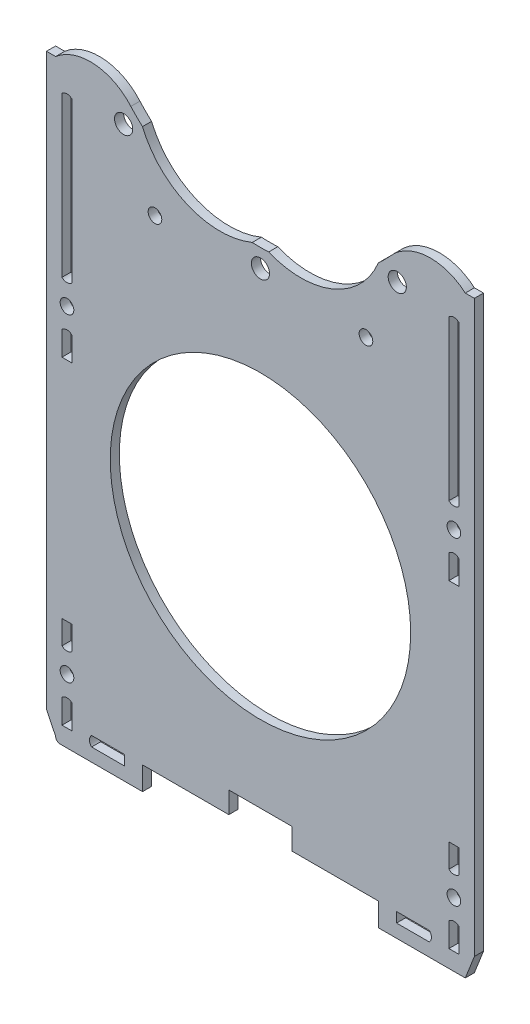
SolidWorks part; units mm, degrees
ref_plane "前视基准面" through (0, 0, 0) normal (0, 0, 1) x (1, 0, 0)
ref_plane "上视基准面" through (0, 0, 0) normal (0, 1, 0) x (1, 0, 0)
ref_plane "右视基准面" through (0, 0, 0) normal (1, 0, 0) x (0, 0, -1)
sketch "草图3" plane through (0, 0, 0) normal (0, 0, 1) x (1, 0, 0)
  line L0 (-37, -95.9902) -> (-37, -96.0902) construction
  line L5 (-37, -93.9902) -> (-30, -93.9902) construction
  line L6 (-37, -93.9902) -> (-37, -95.9902) construction
  line L7 (-37, -95.9902) -> (-30, -95.9902) construction
  line L8 (-30, -93.9902) -> (-30, -95.9902) construction
  line L9 (-37, -96.0902) -> (-37.1, -96.0902) construction
  line L12 (-42.5, -14.9402) -> (-41.8015, -14.9402) construction
  line L19 (-37.1, -96.0902) -> (-29.9, -96.0902)
  line L21 (-37.1, -93.8902) -> (-29.9, -93.8902)
  line L22 (-29.9, -96.0902) -> (-29.9, -93.8902)
  line L111 (-43.6, -9.9902) -> (-43.6, 25.0098)
  line L119 (-41.4, -19.8902) -> (-41.4, -25.1902)
  line L120 (-41.4, -25.1902) -> (-43.6, -25.1902)
  line L121 (-43.6, -25.1902) -> (-43.6, -19.8902)
  line L122 (-47, 31.3171) -> (-47, -93.8902)
  line L124 (37.1, -93.8902) -> (29.9, -93.8902)
  line L136 (37.1, -96.0902) -> (29.9, -96.0902)
  line L147 (30, -93.9902) -> (30, -95.9902) construction
  line L148 (29.9, -96.0902) -> (29.9, -93.8902)
  line L152 (-41.4, 25.0098) -> (-41.4, -9.9902)
  line L153 (37, -96.0902) -> (37.1, -96.0902) construction
  line L154 (37, -93.9902) -> (37, -95.9902) construction
  line L155 (37, -95.9902) -> (37, -96.0902) construction
  line L157 (43.6, -25.1902) -> (43.6, -19.8902)
  line L158 (41.4, -25.1902) -> (43.6, -25.1902)
  line L159 (41.4, -19.8902) -> (41.4, -25.1902)
  line L171 (-25.9, -97.9902) -> (-25.9, -93.8902)
  line L172 (-25.9, -93.8902) -> (-15.9, -93.8902)
  line L180 (0, 10.5098) -> (0, 13.5) construction
  line L181 (-15.9, -93.8902) -> (-6.949, -93.8902)
  line L182 (-6.949, -93.8902) -> (-6.949, -89.1902)
  line L183 (-6.949, -89.1902) -> (6.949, -89.1902)
  line L184 (6.949, -93.8902) -> (6.949, -89.1902)
  line L185 (15.9, -93.8902) -> (6.949, -93.8902)
  line L186 (25.9, -93.8902) -> (15.9, -93.8902)
  line L187 (25.9, -97.9902) -> (25.9, -93.8902)
  line L195 (-25.9, -97.9902) -> (-25.9, -98.9902)
  line L196 (-25.9, -98.9902) -> (-45, -98.9902) construction
  line L197 (-45, -98.9902) -> (-45, -97.9902) construction
  line L198 (25.9, -97.9902) -> (25.9, -98.9902)
  line L199 (25.9, -98.9902) -> (45, -98.9902)
  line L209 (42.5, -9.9902) -> (42.5, -19.8902) construction
  line L210 (-44, -98.9902) -> (-25.9, -98.9902)
  line L212 (0, 56) -> (31.4326, 27.3951) construction
  line L213 (0, 56) -> (28.5728, 24.6019) construction
  line L218 (-45, 31.3171) -> (-47, 31.3171)
  line L220 (-47, -93.8902) -> (-45, -97.9902)
  line L221 (45, 31.3171) -> (47, 31.3171)
  line L223 (47, -93.8902) -> (45, -98.9902)
  line L224 (47, 31.3171) -> (47, -93.8902)
  line L225 (0, -89.1902) -> (0, 10.5098) construction
  line L227 (43.6, -80.0902) -> (41.4, -74.8902) construction
  line L228 (43.6, -74.8902) -> (41.4, -80.0902) construction
  line L229 (42.5, -79.9902) -> (42.5, -74.9902) construction
  line L230 (43.6, -80.0902) -> (43.6, -89.8902) construction
  line L231 (43.6, -95.1902) -> (43.6, -89.8902)
  line L232 (41.4, -95.1902) -> (43.6, -95.1902)
  line L233 (41.4, -89.8902) -> (41.4, -95.1902)
  line L234 (41.4, -74.8902) -> (41.4, -80.0902)
  line L235 (43.6, -74.8902) -> (43.6, -80.0902)
  line L236 (43.6, -74.8902) -> (41.4, -74.8902)
  line L237 (42.5, -79.9902) -> (42.5, -89.8902) construction
  line L239 (-41.4, -80.0902) -> (-43.6, -74.8902) construction
  line L240 (-41.4, -74.8902) -> (-43.6, -80.0902) construction
  line L241 (-42.5, -79.9902) -> (-42.5, -74.9902) construction
  line L242 (-41.4, -80.0902) -> (-41.4, -89.8902) construction
  line L243 (-41.4, -95.1902) -> (-41.4, -89.8902)
  line L244 (-43.6, -95.1902) -> (-41.4, -95.1902)
  line L245 (-43.6, -89.8902) -> (-43.6, -95.1902)
  line L246 (-43.6, -74.8902) -> (-43.6, -80.0902)
  line L247 (-41.4, -74.8902) -> (-41.4, -80.0902)
  line L248 (-41.4, -74.8902) -> (-43.6, -74.8902)
  line L249 (-42.5, -79.9902) -> (-42.5, -89.8902) construction
  line L251 (41.4, 25.0098) -> (41.4, -9.9902)
  line L254 (43.6, -9.9902) -> (43.6, 25.0098)
  arc A14 (-43.6, -19.8902) -> (-41.4, -19.8902) centre (-42.5, -20.9902) cw
  arc A15 (41.4, -19.8902) -> (43.6, -19.8902) centre (42.5, -20.9902) cw
  circle A17 centre (0, 13.5) radius 2
  circle A18 centre (-30.052, 25.948) radius 2
  circle A24 centre (30.052, 25.948) radius 2
  circle A25 centre (-30.052, 86.052) radius 2 [skipped]
  circle A26 centre (0, 98.5) radius 2 [skipped]
  circle A27 centre (30.052, 86.052) radius 2 [skipped]
  circle A28 centre (42.5, 56) radius 2 [skipped]
  arc A29 (37.1, -93.8902) -> (37.1, -96.0902) centre (36, -94.9902) cw
  arc A30 (-37.1, -96.0902) -> (-37.1, -93.8902) centre (-36, -94.9902) cw
  circle A31 centre (-23.1745, 11.9598) radius 1.5
  circle A32 centre (23.1745, 11.9598) radius 1.5
  circle A40 centre (42.5, -14.9402) radius 1.5
  circle A41 centre (-42.5, -14.9402) radius 1.5
  arc A43 (-25.9127, 27.5258) -> (-1.8098, 17.5426) centre (-8.8696, 34.5856) ccw
  arc A44 (1.8098, 17.5426) -> (25.9127, 27.5258) centre (8.8696, 34.5856) ccw
  arc A46 (-25.9127, 27.5258) -> (-28.4742, 30.0873) centre (0, 56) cw
  arc A47 (-1.8098, 17.5426) -> (1.8098, 17.5426) centre (0, 56) ccw
  arc A50 (-44, -98.9902) -> (-45, -97.9902) centre (-44, -97.9902) cw
  circle A51 centre (-42.5, 56) radius 2 [skipped]
  circle A52 centre (0, 56) radius 38.5 construction
  circle A53 centre (0, 56) radius 42.5 construction
  arc A54 (25.9127, 27.5258) -> (28.4742, 30.0873) centre (0, 56) ccw
  arc A55 (28.4742, 30.0873) -> (45, 31.3171) centre (37.352, 22.4393) cw
  arc A56 (-28.4742, 30.0873) -> (-45, 31.3171) centre (-37.352, 22.4393) ccw
  circle A57 centre (0, -39.3402) radius 33
  arc A58 (41.4, -89.8902) -> (43.6, -89.8902) centre (42.5, -90.9902) cw
  arc A59 (41.4, -80.0902) -> (43.6, -80.0902) centre (42.5, -78.9902) ccw
  circle A60 centre (42.5, -84.9402) radius 1.5
  arc A61 (-43.6, -89.8902) -> (-41.4, -89.8902) centre (-42.5, -90.9902) cw
  arc A62 (-43.6, -80.0902) -> (-41.4, -80.0902) centre (-42.5, -78.9902) ccw
  circle A63 centre (-42.5, -84.9402) radius 1.5
  arc A64 (-43.6, -9.9902) -> (-41.4, -9.9902) centre (-42.5, -8.8902) ccw
  arc A65 (43.6, -9.9902) -> (41.4, -9.9902) centre (42.5, -8.8902) cw
  arc A66 (-43.6, 25.0098) -> (-41.4, 25.0098) centre (-42.5, 23.9098) cw
  arc A67 (41.4, 25.0098) -> (43.6, 25.0098) centre (42.5, 23.9098) cw
  point P128 (42.5, -77.4902)
  point P145 (-42.5, -77.4902)
  dimension "D1" = 1
extrude "凸台-拉伸1" add sketch "草图3" along normal blind 2
